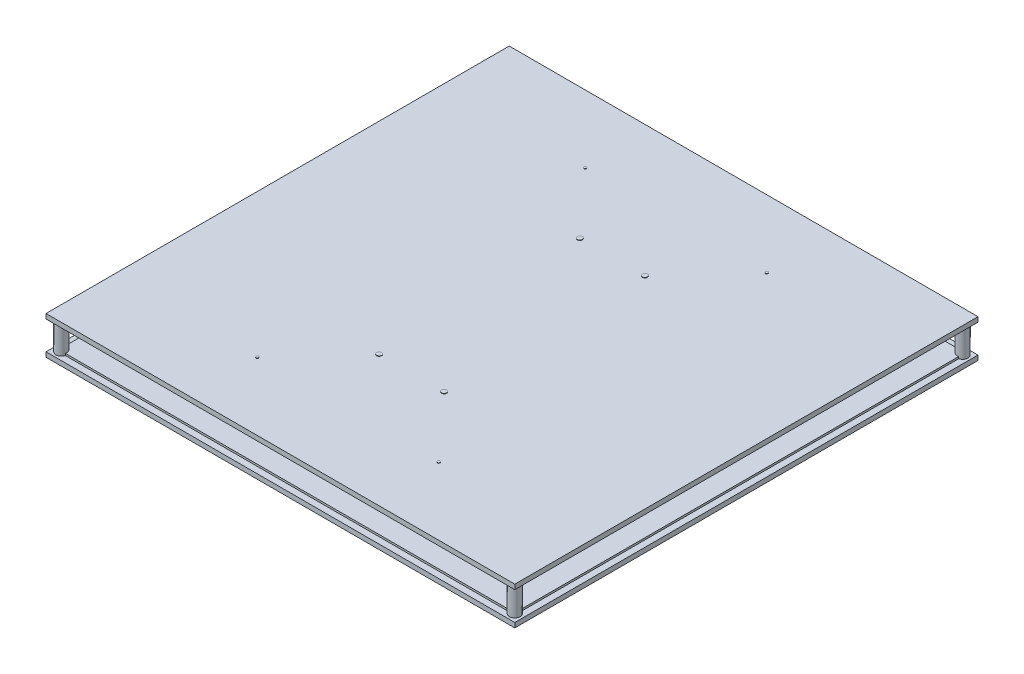
SolidWorks part; units mm, degrees
ref_plane "Front Plane" through (0, 0, 0) normal (0, 0, 1) x (1, 0, 0)
ref_plane "Top Plane" through (0, 0, 0) normal (0, 1, 0) x (1, 0, 0)
ref_plane "Right Plane" through (0, 0, 0) normal (1, 0, 0) x (0, 0, -1)
sketch "Sketch1" plane through (0, 0, 0) normal (0, 1, 0) x (1, 0, 0)
  line L1 (-155.3961, -153.5521) -> (155.3961, -153.5521)
  line L2 (-155.3961, -153.5521) -> (-155.3961, 153.5521)
  line L3 (-155.3961, 153.5521) -> (155.3961, 153.5521)
  line L4 (155.3961, -153.5521) -> (155.3961, 153.5521)
  line L5 (-155.3961, -153.5521) -> (155.3961, 153.5521) construction
  line L6 (-155.3961, 153.5521) -> (155.3961, -153.5521) construction
  point P0 (0, 0)
extrude "Boss-Extrude1" add sketch "Sketch1" along normal blind 3.175 contours L2 L1 L4 L3
sketch "Sketch2" plane through (0, 3.175, 0) normal (0, 1, 0) x (1, 0, 0)
  line L13 (151.1543, 149.3103) -> (-151.1543, 149.3103)
  line L14 (151.1543, 149.3103) -> (151.1543, -149.3103)
  line L15 (151.1543, -149.3103) -> (-151.1543, -149.3103)
  line L16 (-151.1543, 149.3103) -> (-151.1543, -149.3103)
extrude "Boss-Extrude2" add sketch "Sketch2" along normal blind 1.27 contours L14 L13 L16 L15
sketch "Sketch4" plane through (0, 0, -153.5521) normal (0, 0, -1) x (-1, 0, 0)
  line L0 (155.3961, 3.175) -> (155.3961, 25.1714)
  line L1 (-155.3961, 3.175) -> (-155.3961, 25.1714)
sketch "Sketch5" plane through (0, 0, 153.5521) normal (0, 0, 1) x (1, 0, 0)
  line L0 (155.3961, 3.175) -> (155.3961, 25.1714)
  line L1 (-155.3961, 3.175) -> (-155.3961, 25.1714)
sketch3d "3DSketch1"
  line L0 (-155.3961, 25.1714, -153.5521) -> (-155.3961, 25.1714, 153.5521)
  line L1 (-155.3961, 25.1714, 153.5521) -> (155.3961, 25.1714, 153.5521)
  line L2 (155.3961, 25.1714, 153.5521) -> (155.3961, 25.1714, -153.5521)
  line L3 (155.3961, 25.1714, -153.5521) -> (-155.3961, 25.1714, -153.5521)
extrude "Boss-Extrude4" add sketch "3DSketch1" along direction (0, -1, 0) on the side of the normal blind 3.175 separate body contours L0 L1 L2 L3
sketch "Sketch6" plane through (0, 25.1714, 0) normal (0, 1, 0) x (1, 0, 0)
  line L1 (155.3961, 153.5521) -> (-155.3961, 153.5521) construction
  line L5 (0, -153.5521) -> (0, 153.5521)
  line L6 (-155.3961, -153.5521) -> (155.3961, -153.5521) construction
  line L7 (-155.3961, 0) -> (155.3961, 0)
  line L8 (-155.3961, 153.5521) -> (-155.3961, -153.5521) construction
  line L9 (155.3961, -153.5521) -> (155.3961, 153.5521) construction
  circle A0 centre (60.1461, 108.7163) radius 0.911
  circle A1 centre (21.5381, 66.5523) radius 1.6837
  circle A2 centre (-21.5381, 66.5523) radius 1.6837
  circle A3 centre (-60.1461, 108.7163) radius 0.911
  circle A4 centre (21.5381, -66.5523) radius 1.6837
  circle A5 centre (60.1461, -108.7163) radius 0.911
  circle A6 centre (-21.5381, -66.5523) radius 1.6837
  circle A7 centre (-60.1461, -108.7163) radius 0.911
  dimension "D1" = 44.8358
  dimension "D2" = 44.8358
  dimension "D3" = 44.8358
  dimension "D4" = 44.8358
  dimension "D5" = 86.9998
  dimension "D6" = 3.3675
extrude "Boss-Extrude7" add sketch "Sketch6" along normal blind 0.254 contours A7 | A6 | A3 | A2 | A1 | A0 | A4 | A5
sketch "Sketch7" plane through (0, 0, 0) normal (0, -1, 0) x (1, 0, 0)
  line L0 (-155.3961, 153.5521) -> (-150.3161, 153.5521)
  line L1 (-155.3961, 153.5521) -> (155.3961, 153.5521) construction
  circle A0 centre (-150.3161, 148.4721) radius 3.556
  circle A1 centre (150.3161, 148.4721) radius 3.556
  circle A2 centre (150.3161, -148.4721) radius 3.556
  circle A3 centre (-150.3161, -148.4721) radius 3.556
extrude "Boss-Extrude8" add sketch "Sketch7" against normal blind 23.876 contours A3 | A2 | A1 | A0
